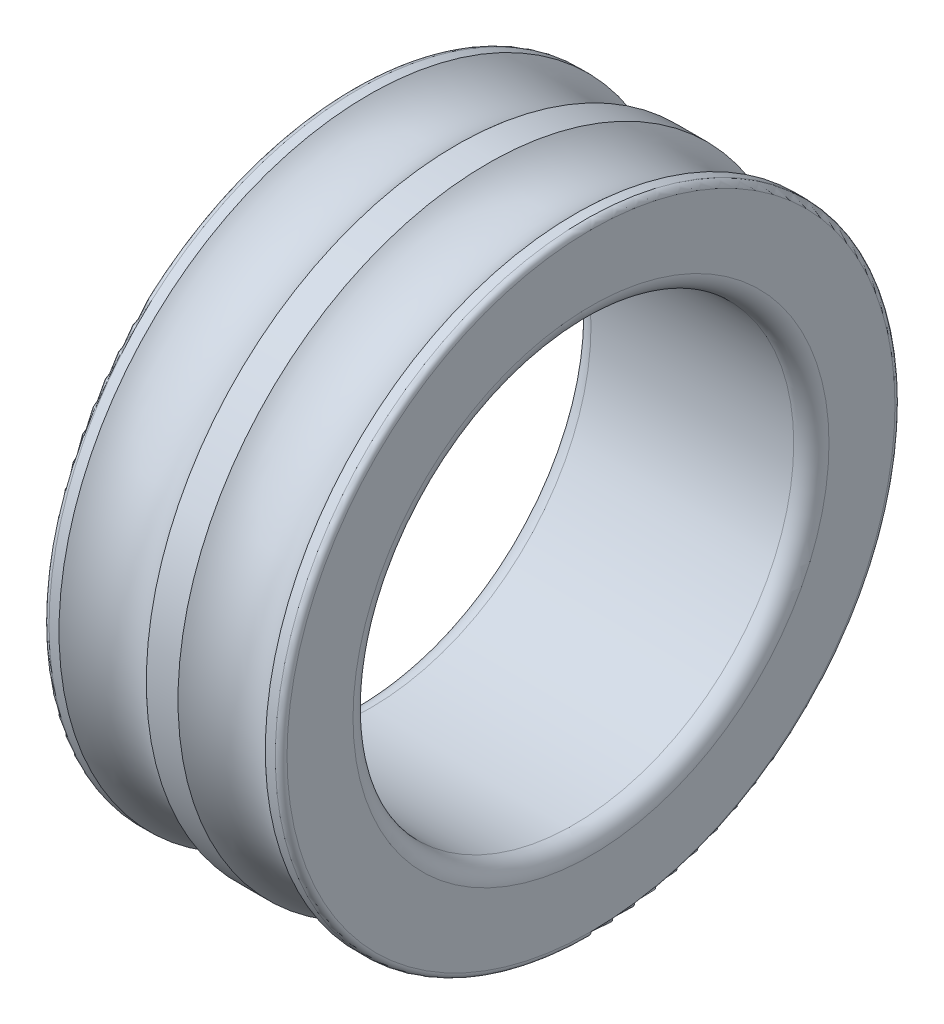
SolidWorks part; units mm, degrees
ref_plane "Front Plane" through (0, 0, 0) normal (0, 0, 1) x (1, 0, 0)
ref_plane "Top Plane" through (0, 0, 0) normal (0, 1, 0) x (1, 0, 0)
ref_plane "Right Plane" through (0, 0, 0) normal (1, 0, 0) x (0, 0, -1)
sketch "Sketch1" plane through (0, 0, 0) normal (0, 0, 1) x (1, 0, 0)
  line L0 (1.7983, 35.15) -> (0, 35.15)
  line L1 (0, 35.15) -> (0, 25)
  line L2 (0, 25) -> (27, 25)
  line L3 (27, 25) -> (27, 35.15)
  line L4 (27, 35.15) -> (25.2017, 35.15)
  line L5 (15.2983, 35.15) -> (11.7017, 35.15)
  line L6 (0, 0) -> (27, 0) construction
  arc A0 (25.2017, 35.15) -> (15.2983, 35.15) centre (20.25, 40.2995) cw
  arc A1 (11.7017, 35.15) -> (1.7983, 35.15) centre (6.75, 40.2995) cw
revolve "Revolve1" add sketch "Sketch1" angle 360 about L6
fillet "Fillet1" radius 2 2 edges at (0, 0, -25) (27, 0, -25)
fillet "Fillet2" radius 0.6667 2 edges at (0, 0, -35.15) (27, 0, -35.15)
